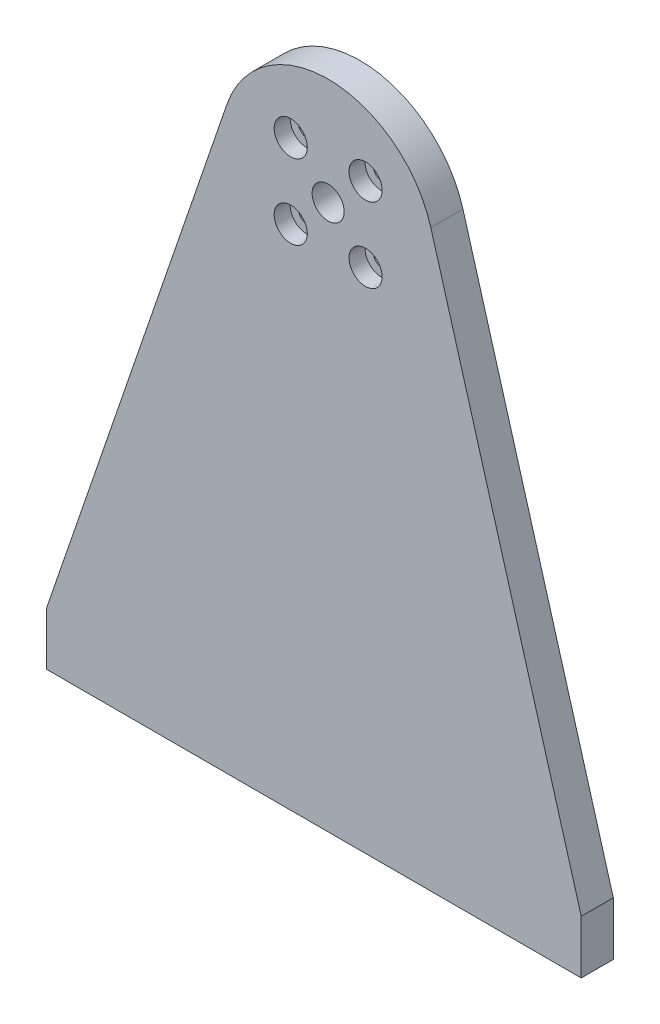
SolidWorks part; units mm, degrees
ref_plane "前视基准面" through (0, 0, 0) normal (0, 0, 1) x (1, 0, 0)
ref_plane "上视基准面" through (0, 0, 0) normal (0, 1, 0) x (1, 0, 0)
ref_plane "右视基准面" through (0, 0, 0) normal (1, 0, 0) x (0, 0, -1)
other "Configuration Table"
sketch "草图1" plane through (0, 0, 0) normal (0, 0, 1) x (1, 0, 0)
  line L5 (55.4928, 10.01) -> (83.624, -87.4969)
  line L6 (17.3564, 10.9489) -> (-16.376, -87.4969)
  line L9 (83.624, -87.4969) -> (83.624, -97.4969)
  line L10 (83.624, -97.4969) -> (-16.376, -97.4969)
  line L11 (-16.376, -97.4969) -> (-16.376, -87.4969)
  arc A0 (55.4928, 10.01) -> (17.3564, 10.9489) centre (36.2765, 4.466) ccw
  circle A2 centre (36.2765, 4.466) radius 3
  point P0 (0, 0)
extrude "凸台-拉伸1" add sketch "草图1" along normal blind 6
sketch "草图2" plane through (0, 0, 6) normal (0, 0, 1) x (1, 0, 0)
  line L0 (36.2765, 4.466) -> (36.2765, 16.549) construction
  line L5 (36.2765, 4.466) -> (44.4343, 4.466) construction
  circle A2 centre (29.2765, 11.466) radius 3.1
  circle A3 centre (43.2765, 11.466) radius 3.1
  circle A4 centre (43.2765, -2.534) radius 3.1
  circle A5 centre (29.2765, -2.534) radius 3.1
extrude "切除-拉伸6" cut sketch "草图2" against normal blind 3
sketch "草图4" plane through (0, 0, 3) normal (0, 0, 1) x (1, 0, 0)
  circle A0 centre (43.2765, 11.466) radius 1.5 construction
  circle A1 centre (43.2765, 11.466) radius 1.5
  circle A2 centre (43.2765, -2.534) radius 1.5 construction
  circle A3 centre (43.2765, -2.534) radius 1.5
  circle A4 centre (29.2765, -2.534) radius 1.5 construction
  circle A5 centre (29.2765, -2.534) radius 1.5
  circle A6 centre (29.2765, 11.466) radius 1.5 construction
  circle A7 centre (29.2765, 11.466) radius 1.5
extrude "切除-拉伸7" cut sketch "草图4" against normal through all
